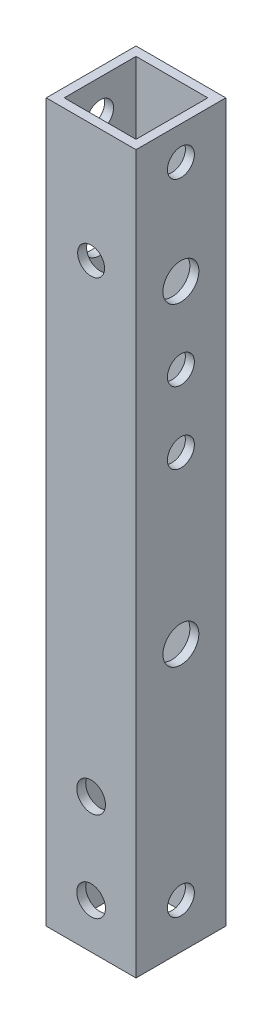
SolidWorks part; units mm, degrees
material "1060 合金"
ref_plane "正面" through (0, 0, 0) normal (0, 0, 1) x (1, 0, 0)
ref_plane "平面" through (0, 0, 0) normal (0, 1, 0) x (1, 0, 0)
ref_plane "右側面" through (0, 0, 0) normal (1, 0, 0) x (0, 0, -1)
sketch "ｽｹｯﾁ1" plane through (0, 0, 0) normal (0, 1, 0) x (1, 0, 0)
  line L1 (-5, -5) -> (5, -5)
  line L2 (-5, -5) -> (-5, 5)
  line L3 (-5, 5) -> (5, 5)
  line L4 (5, -5) -> (5, 5)
  line L5 (-5, -5) -> (5, 5) construction
  line L6 (-5, 5) -> (5, -5) construction
  point P0 (0, 0)
  dimension "D1" = 10
extrude "押し出し-薄板1" add sketch "ｽｹｯﾁ1" along normal blind 104.9 thin thin type one direction reverse wall 1
sketch "ｽｹｯﾁ2" plane through (0, 0, 5) normal (0, 0, 1) x (1, 0, 0)
  line L0 (0, 0) -> (0, 104.9) construction
  line L1 (-5, 104.9) -> (5, 104.9) construction
  line L2 (-5, 0) -> (5, 0) construction
  circle A1 centre (0, 5) radius 1.6
  circle A4 centre (0, 15) radius 1.6
  circle A5 centre (0, 92.95) radius 1.5
  circle A6 centre (0, 66.7) radius 1.5
  circle A7 centre (0, 99.9) radius 1.5
  dimension "D1" = 5
  dimension "D2" = 3.2
  dimension "D3" = 11.95
  dimension "D4" = 3
  dimension "D5" = 38.2
  dimension "D6" = 6.95
  dimension "D7" = 10
extrude "ｶｯﾄ - 押し出し1" cut sketch "ｽｹｯﾁ2" against normal through all
sketch "ｽｹｯﾁ3" plane through (5, 0, 0) normal (1, 0, 0) x (0, 0, -1)
  line L0 (0, 0) -> (0, 104.9) construction
  line L1 (-5, 0) -> (5, 0) construction
  line L2 (-5, 104.9) -> (5, 104.9) construction
  circle A15 centre (0, 76.2) radius 1.5
  circle A17 centre (0, 5) radius 1.5
  circle A18 centre (0, 64.7) radius 2
  circle A19 centre (0, 29.7) radius 2
  circle A20 centre (0, 48.2) radius 1.5
  circle A21 centre (0, 56.2) radius 1.5
  dimension "D2" = 24.7
  dimension "D3" = 35
  dimension "D4" = 11.5
  dimension "D5" = 3
  dimension "D6" = 4
  dimension "D7" = 48.2
  dimension "D8" = 8
  dimension "D9" = 3
  dimension "D11" = 5
  dimension "D12" = 3
extrude "ｶｯﾄ - 押し出し2" cut sketch "ｽｹｯﾁ3" against normal through all
sketch "ｽｹｯﾁ4" plane through (0, 104.9, 0) normal (0, 1, 0) x (1, 0, 0)
  line L1 (-5, -5) -> (5, -5)
  line L2 (-5, -5) -> (-5, 5)
  line L3 (-5, 5) -> (5, 5)
  line L4 (5, -5) -> (5, 5)
  line L5 (-5, -5) -> (5, 5) construction
  line L6 (-5, 5) -> (5, -5) construction
  point P0 (0, 0)
extrude "ｶｯﾄ - 押し出し3" cut sketch "ｽｹｯﾁ4" against normal blind 25
